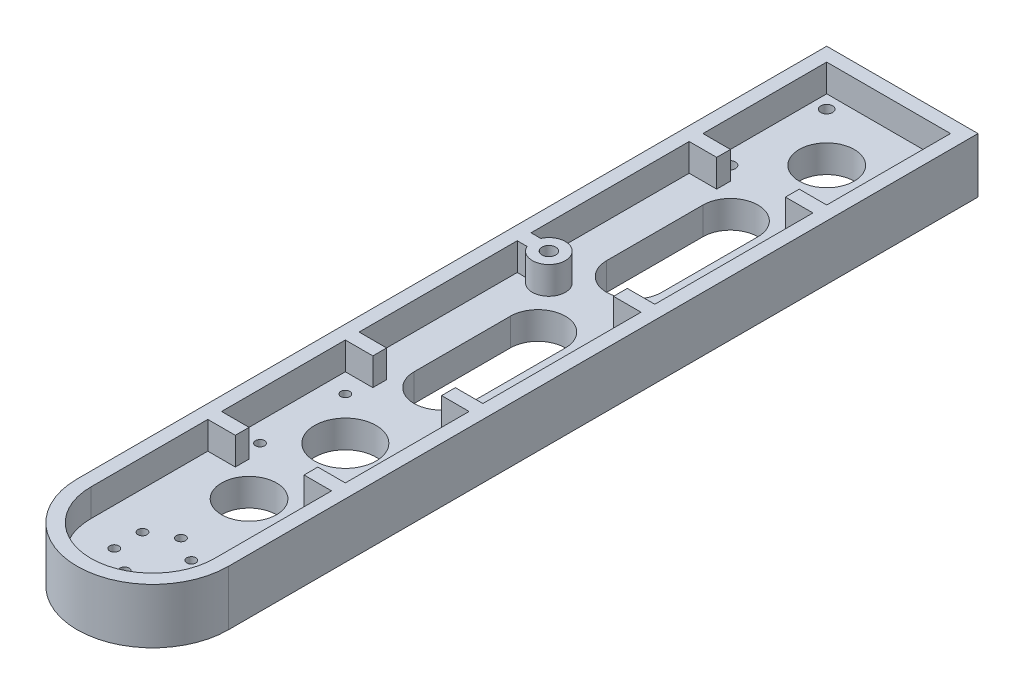
SolidWorks part; units mm, degrees
ref_plane "前视基准面" through (0, 0, 0) normal (0, 0, 1) x (1, 0, 0)
ref_plane "上视基准面" through (0, 0, 0) normal (0, 1, 0) x (1, 0, 0)
ref_plane "右视基准面" through (0, 0, 0) normal (1, 0, 0) x (0, 0, -1)
sketch "草图1" plane through (0, 0, 0) normal (0, 1, 0) x (1, 0, 0)
  line L0 (-27.5, 0) -> (-27.5, 272.5)
  line L1 (0, 0) -> (0, 245) construction
  line L2 (27.5, 272.5) -> (27.5, 0)
  line L3 (-27.5, 272.5) -> (27.5, 272.5)
  line L4 (0, 105) -> (0, 140) construction
  line L5 (-17.6777, 227.3223) -> (17.6777, 227.3223) construction
  line L6 (-17.6777, 227.3223) -> (-17.6777, 262.6777) construction
  line L7 (-17.6777, 262.6777) -> (17.6777, 262.6777) construction
  line L8 (17.6777, 227.3223) -> (17.6777, 262.6777) construction
  line L9 (-17.6777, 227.3223) -> (17.6777, 262.6777) construction
  line L10 (-17.6777, 262.6777) -> (17.6777, 227.3223) construction
  line L11 (-15.5, 54.5) -> (15.5, 54.5) construction
  line L12 (-15.5, 54.5) -> (-15.5, 85.5) construction
  line L13 (-15.5, 85.5) -> (15.5, 85.5) construction
  line L14 (15.5, 54.5) -> (15.5, 85.5) construction
  line L15 (-15.5, 54.5) -> (15.5, 85.5) construction
  line L16 (-15.5, 85.5) -> (15.5, 54.5) construction
  line L17 (-10, 105) -> (-10, 140)
  line L18 (10, 105) -> (10, 140)
  line L19 (0, 175) -> (0, 210) construction
  line L20 (-10, 175) -> (-10, 210)
  line L21 (10, 175) -> (10, 210)
  line L22 (0, 157.5) -> (-13.5, 157.5) construction
  arc A3 (-27.5, 0) -> (27.5, 0) centre (0, 0) ccw
  circle A4 centre (0, 0) radius 10.25 construction
  circle A5 centre (0, 10.25) radius 1.65
  circle A6 centre (8.8768, 5.125) radius 1.65
  circle A7 centre (8.8768, -5.125) radius 1.65
  circle A8 centre (0, -10.25) radius 1.65
  circle A9 centre (-8.8768, -5.125) radius 1.65
  circle A10 centre (-8.8768, 5.125) radius 1.65
  circle A11 centre (-17.6777, 262.6777) radius 2.15
  circle A12 centre (17.6777, 262.6777) radius 2.15
  circle A13 centre (17.6777, 227.3223) radius 2.15
  circle A14 centre (-17.6777, 227.3223) radius 2.15
  circle A15 centre (0, 245) radius 10
  circle A16 centre (-15.5, 85.5) radius 1.65
  circle A17 centre (15.5, 85.5) radius 1.65
  circle A18 centre (15.5, 54.5) radius 1.65
  circle A19 centre (-15.5, 54.5) radius 1.65
  circle A20 centre (0, 70) radius 11.2
  circle A21 centre (0, 35) radius 10
  arc A22 (-10, 105) -> (10, 105) centre (0, 105) ccw
  arc A23 (10, 140) -> (-10, 140) centre (0, 140) ccw
  arc A24 (-10, 175) -> (10, 175) centre (0, 175) ccw
  arc A25 (10, 210) -> (-10, 210) centre (0, 210) ccw
  circle A26 centre (-13.5, 157.5) radius 2.65
  point P22 (0, 0)
  point P27 (0, 70)
  point P50 (0, 122.5)
  point P55 (0, 192.5)
  point P65 (0, 165)
  dimension "D1" = 55
  dimension "D3" = 20.5
  dimension "D4" = 3.3
  dimension "D8" = 4.3
  dimension "D10" = 20
  dimension "D12" = 3.3
  dimension "D15" = 22.4
  dimension "D16" = 20
  dimension "D17" = 35
  dimension "D18" = 35
  dimension "D21" = 10
  dimension "D22" = 5.3
  dimension "D2" = 245
  dimension "D6" = 27.5
  dimension "D7" = 50
  dimension "D13" = 31
  dimension "D14" = 70
  dimension "D19" = 35
  dimension "D20" = 35
  dimension "D23" = 13.5
  dimension "D24" = 7.5
  dimension "D5" = 6
  dimension "D9" = 4
  dimension "D11" = 4
extrude "凸台-拉伸1" add sketch "草图1" along normal blind 10
sketch "草图2" plane through (0, 10, 0) normal (0, 1, 0) x (1, 0, 0)
  line L0 (-27.5, 272.5) -> (27.5, 272.5)
  line L1 (-22.5, 222.5) -> (22.5, 222.5)
  line L2 (-22.5, 222.5) -> (-22.5, 267.5)
  line L3 (-22.5, 267.5) -> (22.5, 267.5)
  line L4 (22.5, 222.5) -> (22.5, 267.5)
  line L5 (-22.5, 222.5) -> (22.5, 267.5) construction
  line L6 (-22.5, 267.5) -> (22.5, 222.5) construction
  line L7 (27.5, 272.5) -> (27.5, 0)
  line L8 (-27.5, 0) -> (-27.5, 272.5)
  line L9 (-22.5, 0) -> (-22.5, 222.5)
  line L10 (22.5, 222.5) -> (22.5, 0)
  arc A1 (-27.5, 0) -> (27.5, 0) centre (0, 0) ccw
  arc A2 (-27.5, 0) -> (27.5, 0) centre (0, 0) ccw construction
  arc A3 (-22.5, 0) -> (22.5, 0) centre (0, 0) ccw
  point P3 (0, 245)
  arc M15 (-27.5, 0) -> (27.5, 0) centre (0, 0) ccw
  line M16 (27.5, 0) -> (27.5, 272.5)
  line M17 (27.5, 272.5) -> (-27.5, 272.5)
  line M18 (-27.5, 272.5) -> (-27.5, 0)
  dimension "D2" = 45
extrude "凸台-拉伸2" add sketch "草图2" along normal blind 10 contours A3 L9 L2 L3 L4 L10 M18 M15 M16 M17
sketch "草图4" plane through (0, 10, 0) normal (0, 1, 0) x (1, 0, 0)
  line L0 (22.5, 0) -> (22.5, 267.5) construction
  line L1 (-22.5, 47.5) -> (22.5, 47.5) construction
  line L2 (-22.5, 47.5) -> (-22.5, 92.5) construction
  line L3 (-22.5, 92.5) -> (22.5, 92.5) construction
  line L4 (22.5, 47.5) -> (22.5, 92.5) construction
  line L5 (-22.5, 47.5) -> (22.5, 92.5) construction
  line L6 (-22.5, 92.5) -> (22.5, 47.5) construction
  line L7 (0, 150) -> (0, 165) construction
  line L8 (-22.5, 92.5) -> (-12.5, 92.5)
  line L9 (-22.5, 92.5) -> (-22.5, 97.5)
  line L10 (-22.5, 97.5) -> (-12.5, 97.5)
  line L11 (-12.5, 92.5) -> (-12.5, 97.5)
  line L12 (-22.5, 222.5) -> (22.5, 222.5) construction
  line L13 (-22.5, 222.5) -> (-22.5, 267.5) construction
  line L14 (-22.5, 267.5) -> (22.5, 267.5) construction
  line L15 (22.5, 222.5) -> (22.5, 267.5) construction
  line L16 (-22.5, 222.5) -> (22.5, 267.5) construction
  line L17 (-22.5, 267.5) -> (22.5, 222.5) construction
  line L18 (-22.5, 222.5) -> (-12.5, 222.5)
  line L19 (-22.5, 222.5) -> (-22.5, 217.5)
  line L20 (-22.5, 217.5) -> (-12.5, 217.5)
  line L21 (-12.5, 222.5) -> (-12.5, 217.5)
  line L22 (22.5, 222.5) -> (12.5, 222.5)
  line L23 (22.5, 222.5) -> (22.5, 217.5)
  line L24 (22.5, 217.5) -> (12.5, 217.5)
  line L25 (12.5, 222.5) -> (12.5, 217.5)
  line L26 (22.5, 92.5) -> (12.5, 92.5)
  line L27 (22.5, 92.5) -> (22.5, 97.5)
  line L28 (22.5, 97.5) -> (12.5, 97.5)
  line L29 (12.5, 92.5) -> (12.5, 97.5)
  line L30 (-22.5, 47.5) -> (-12.5, 47.5)
  line L31 (-22.5, 47.5) -> (-22.5, 42.5)
  line L32 (-22.5, 42.5) -> (-12.5, 42.5)
  line L33 (-12.5, 47.5) -> (-12.5, 42.5)
  line L34 (22.5, 47.5) -> (12.5, 47.5)
  line L35 (22.5, 47.5) -> (22.5, 42.5)
  line L36 (22.5, 42.5) -> (12.5, 42.5)
  line L37 (12.5, 47.5) -> (12.5, 42.5)
  line L38 (-22.5, 0) -> (-22.5, 267.5) construction
  line L40 (-22.5, 155) -> (-22.5, 160)
  line L42 (-12.5, 155) -> (-12.5, 160) construction
  line L43 (-12.5, 157.5) -> (12.5, 157.5) construction
  line L44 (22.5, 155) -> (12.5, 155)
  line L45 (22.5, 155) -> (22.5, 160)
  line L46 (22.5, 160) -> (12.5, 160)
  line L47 (12.5, 155) -> (12.5, 160)
  line L50 (-18.9544, 160) -> (-22.5, 160)
  line L51 (-18.9544, 155) -> (-22.5, 155)
  line L52 (-12.5, 157.5) -> (-22.5, 157.5) construction
  arc A0 (10, 140) -> (-10, 140) centre (0, 140) ccw construction
  arc A1 (-10, 175) -> (10, 175) centre (0, 175) ccw construction
  circle A2 centre (-13.5, 157.5) radius 2.5
  arc A4 (-18.9544, 160) -> (-18.9544, 155) centre (-13.5, 157.5) cw
  point P0 (0, 70)
  point P11 (0, 245)
  point P53 (0, 157.5)
  dimension "D3" = 13.5
  dimension "D4" = 5
  dimension "D5" = 6
  dimension "D1" = 10
  dimension "D2" = 5
extrude "凸台-拉伸3" add sketch "草图4" along normal up to surface (10 mm away) up to face at (0, 20, -128.125)
